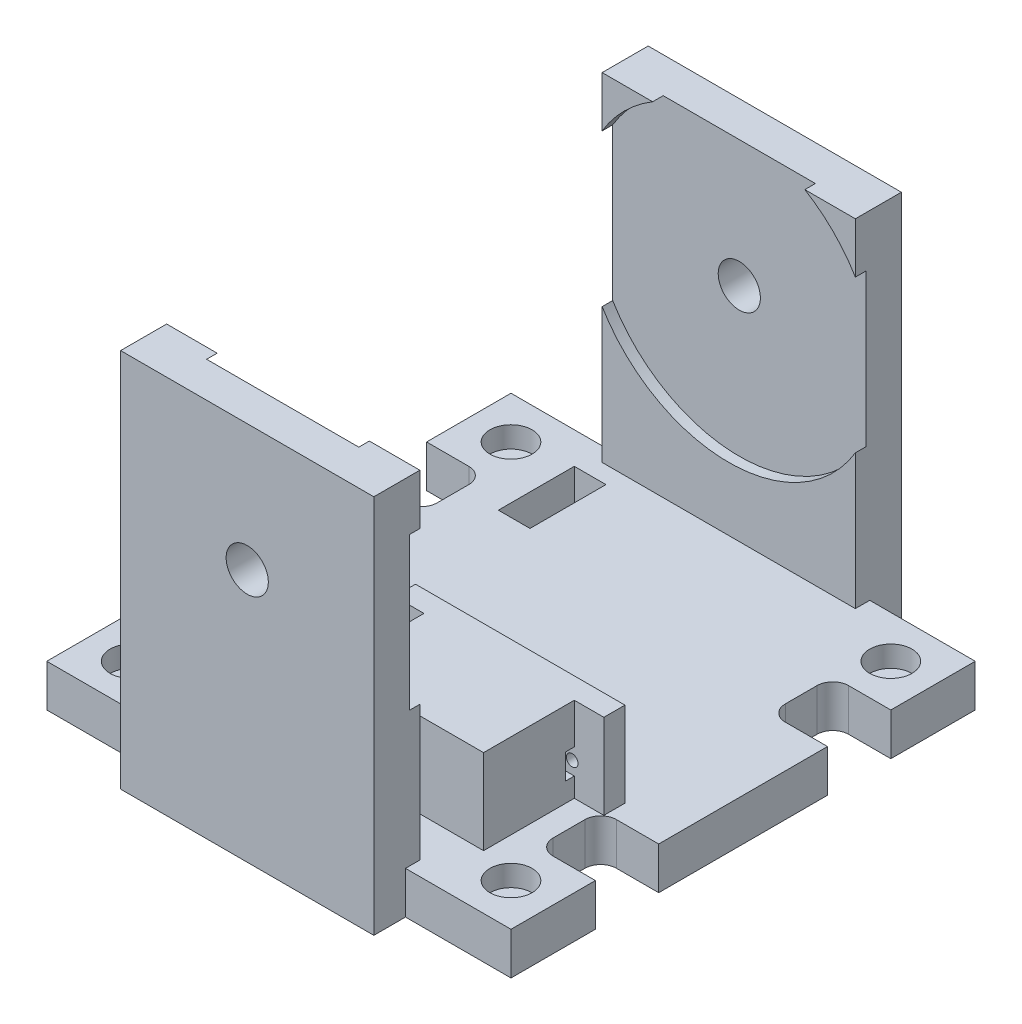
SolidWorks part; units mm, degrees
ref_plane "Front Plane" through (0, 0, 0) normal (0, 0, 1) x (1, 0, 0)
ref_plane "Top Plane" through (0, 0, 0) normal (0, 1, 0) x (1, 0, 0)
ref_plane "Right Plane" through (0, 0, 0) normal (1, 0, 0) x (0, 0, -1)
sketch "Sketch1" plane through (0, 0, 0) normal (0, 1, 0) x (1, 0, 0)
  line L0 (-44, 28) -> (-36, 28)
  line L1 (44, -44) -> (-44, -44)
  line L2 (44, -44) -> (44, 44) construction
  line L3 (44, 44) -> (-44, 44)
  line L4 (-44, -44) -> (-44, 44) construction
  line L5 (44, -44) -> (-44, 44) construction
  line L6 (44, 44) -> (-44, -44) construction
  line L7 (-33, 25) -> (-33, -25) construction
  line L8 (-36, -28) -> (-44, -28)
  line L9 (-33, 0) -> (0, 0) construction
  line L10 (0, 44) -> (0, -44) construction
  line L11 (-44, 28) -> (-44, 44)
  line L12 (-44, -28) -> (-44, -44)
  line L13 (44, -28) -> (44, -44)
  line L14 (44, 28) -> (44, 44)
  line L15 (36, -28) -> (44, -28)
  line L16 (33, 25) -> (33, -25) construction
  line L17 (44, 28) -> (36, 28)
  line L18 (-33, 25) -> (-33, 19)
  line L19 (-36, 16) -> (-44, 16)
  line L20 (-44, 16) -> (-44, -16)
  line L21 (-44, -16) -> (-36, -16)
  line L22 (-33, -19) -> (-33, -25)
  line L23 (33, -19) -> (33, -25)
  line L24 (44, -16) -> (36, -16)
  line L25 (44, 16) -> (44, -16)
  line L26 (36, 16) -> (44, 16)
  line L27 (33, 19) -> (33, 25)
  arc A0 (-36, 28) -> (-33, 25) centre (-36, 25) cw
  arc A1 (-33, -25) -> (-36, -28) centre (-36, -25) cw
  arc A2 (33, -25) -> (36, -28) centre (36, -25) ccw
  arc A3 (36, 28) -> (33, 25) centre (36, 25) ccw
  arc A4 (-33, 19) -> (-36, 16) centre (-36, 19) cw
  arc A5 (-36, -16) -> (-33, -19) centre (-36, -19) cw
  arc A6 (36, -16) -> (33, -19) centre (36, -19) ccw
  arc A7 (33, 19) -> (36, 16) centre (36, 19) ccw
  point P0 (0, 0)
  dimension "D1" = 88
  dimension "D2" = 16
  dimension "D3" = 8
  dimension "D4" = 3
  dimension "D5" = 12
  dimension "D6" = 12
extrude "Boss-Extrude1" add sketch "Sketch1" along normal blind 8
sketch "Sketch2" plane through (0, 8, 0) normal (0, 1, 0) x (1, 0, 0)
  line L0 (-44, 44) -> (-44, 28) construction
  line L1 (44, 44) -> (-44, 44) construction
  line L2 (-44, 0) -> (0, 0) construction
  line L3 (-44, 16) -> (-44, -16) construction
  line L4 (0, 0) -> (0, 44) construction
  circle A0 centre (-36, 36) radius 1.651
  circle A1 centre (36, 36) radius 1.651
  circle A2 centre (36, -36) radius 1.651
  circle A3 centre (-36, -36) radius 1.651
  dimension "D3" = 3.302
  dimension "D1" = 8
  dimension "D2" = 8
extrude "Cut-Extrude1" cut sketch "Sketch2" against normal through all
sketch "Sketch3" plane through (0, 8, 0) normal (0, 1, 0) x (1, 0, 0)
  circle A0 centre (-36, 36) radius 4
  circle A1 centre (36, 36) radius 4
  circle A2 centre (36, -36) radius 4
  circle A3 centre (-36, -36) radius 4
  dimension "D1" = 8
extrude "Cut-Extrude2" cut sketch "Sketch3" against normal blind 4
sketch "Sketch4" plane through (0, 8, 0) normal (0, 1, 0) x (1, 0, 0)
  line L0 (0, -12.5) -> (3, -12.5)
  line L1 (28.5, -33.7) -> (0, -33.7)
  line L2 (28.5, -33.7) -> (28.5, -12.5) construction
  line L3 (28.5, -12.5) -> (0, -12.5) construction
  line L4 (0, -33.7) -> (0, -12.5) construction
  line L5 (28.5, -33.7) -> (0, -12.5) construction
  line L6 (28.5, -12.5) -> (0, -33.7) construction
  line L7 (3, -12.5) -> (3, -30.7)
  line L8 (3, -30.7) -> (25.5, -30.7)
  line L9 (25.5, -30.7) -> (25.5, -12.5)
  line L10 (25.5, -12.5) -> (28.5, -12.5)
  line L11 (0, -12.5) -> (-5.6, -12.5)
  line L12 (-5.6, -12.5) -> (-5.6, -16.5)
  line L13 (-5.6, -16.5) -> (0, -16.5)
  line L14 (0, -16.5) -> (0, -33.7)
  line L15 (28.5, -12.5) -> (34.1, -12.5)
  line L16 (34.1, -12.5) -> (34.1, -16.5)
  line L17 (34.1, -16.5) -> (28.5, -16.5)
  line L18 (28.5, -16.5) -> (28.5, -33.7)
  point P0 (14.25, -23.1)
  dimension "D1" = 28.5
  dimension "D2" = 21.2
  dimension "D3" = 33.7
  dimension "D4" = 3
  dimension "D5" = 3
  dimension "D6" = 4
  dimension "D7" = 5.6
extrude "Boss-Extrude2" add sketch "Sketch4" along normal blind 12.1
sketch "Sketch5" plane through (0, 20.1, 0) normal (0, 1, 0) x (1, 0, 0)
  line L0 (3, -12.5) -> (25.5, -12.5)
  line L12 (3, -12.5) -> (-5.6, -12.5)
  line L13 (-5.6, -12.5) -> (-5.6, -16.5)
  line L14 (-5.6, -16.5) -> (0, -16.5)
  line L15 (0, -16.5) -> (0, -33.7)
  line L16 (0, -33.7) -> (28.5, -33.7)
  line L17 (28.5, -33.7) -> (28.5, -16.5)
  line L18 (28.5, -16.5) -> (34.1, -16.5)
  line L19 (34.1, -16.5) -> (34.1, -12.5)
  line L20 (34.1, -12.5) -> (25.5, -12.5)
  line L21 (25.5, -12.5) -> (25.5, -30.7)
  line L22 (25.5, -30.7) -> (3, -30.7)
  line L23 (3, -30.7) -> (3, -12.5)
  line L24 (3, -12.5) -> (-5.6, -12.5)
  line L25 (-5.6, -12.5) -> (-5.6, -16.5)
  line L26 (-5.6, -16.5) -> (0, -16.5)
  line L27 (0, -16.5) -> (0, -33.7)
  line L28 (0, -33.7) -> (28.5, -33.7)
  line L29 (28.5, -33.7) -> (28.5, -16.5)
  line L30 (28.5, -16.5) -> (34.1, -16.5)
  line L31 (34.1, -16.5) -> (34.1, -12.5)
  line L32 (34.1, -12.5) -> (25.5, -12.5)
  line L33 (25.5, -12.5) -> (25.5, -30.7) construction
  line L34 (25.5, -30.7) -> (3, -30.7) construction
  line L35 (3, -30.7) -> (3, -12.5) construction
  dimension "D1" = 0
extrude "Boss-Extrude3" add sketch "Sketch5" along normal blind 4
sketch "Sketch6" plane through (0, 0, 12.5) normal (0, 0, -1) x (-1, 0, 0)
  line L0 (-28.1, 14.05) -> (-0.4, 14.05) construction
  line L1 (-25.5, 20.1) -> (-25.5, 8) construction
  line L2 (-14.25, 14.05) -> (-14.25, 8) construction
  line L3 (-25.5, 8) -> (-3, 8) construction
  circle A0 centre (-28.1, 14.05) radius 1.1
  circle A1 centre (-0.4, 14.05) radius 1.1
  point P4 (-25.5, 14.05)
  dimension "D1" = 2.2
  dimension "D2" = 27.7
extrude "Cut-Extrude4" cut sketch "Sketch6" against normal blind 4
sketch "Sketch7" plane through (28.5, 0, 0) normal (1, 0, 0) x (0, 0, -1)
  line L1 (-18.1764, 16.4376) -> (-16.5, 16.4376)
  line L2 (-18.1764, 16.4376) -> (-18.1764, 11.6624)
  line L3 (-18.1764, 11.6624) -> (-16.5, 11.6624)
  line L4 (-16.5, 16.4376) -> (-16.5, 11.6624)
  line L5 (-18.1764, 16.4376) -> (-16.5, 11.6624) construction
  line L6 (-18.1764, 11.6624) -> (-16.5, 16.4376) construction
  line L7 (-16.5, 13.0253) -> (-16.5, 8) construction
  line L8 (-12.5, 12.95) -> (-12.5, 15.15) construction
  line L9 (-12.5, 12.95) -> (-12.5, 15.15) construction
  line L10 (-17.3382, 14.05) -> (-12.5, 14.05) construction
  point P0 (-17.3382, 14.05)
  dimension "D1" = 4.7752
  dimension "D2" = 1.6764
extrude "Cut-Extrude5" cut sketch "Sketch7" against normal through all
sketch "Sketch8" plane through (0, 8, 0) normal (0, 1, 0) x (1, 0, 0)
  line L0 (-44, -44) -> (44, -44) construction
  line L1 (24, 41.275) -> (-24, 41.275)
  line L2 (24, 41.275) -> (24, 44)
  line L3 (24, 44) -> (-24, 44)
  line L4 (-24, 41.275) -> (-24, 44)
  line L5 (24, 41.275) -> (-24, 44) construction
  line L6 (24, 44) -> (-24, 41.275) construction
  line L7 (24, -44) -> (-24, -44)
  line L8 (24, -44) -> (24, -41.275)
  line L9 (24, -41.275) -> (-24, -41.275)
  line L10 (-24, -44) -> (-24, -41.275)
  line L11 (24, -44) -> (-24, -41.275) construction
  line L12 (24, -41.275) -> (-24, -44) construction
  line L13 (44, 44) -> (-44, 44) construction
  line L14 (0, 41.275) -> (0, 0) construction
  point P0 (0, 42.6375)
  point P5 (0, -42.6375)
  dimension "D1" = 82.55
  dimension "D2" = 48
extrude "Boss-Extrude4" add sketch "Sketch8" along normal blind 64
sketch "Sketch9" plane through (0, 0, 44) normal (0, 0, 1) x (1, 0, 0)
  line L0 (-44, 0) -> (44, 0) construction
  line L1 (24, 0) -> (-24, 0)
  line L2 (24, 0) -> (24, 72)
  line L3 (24, 72) -> (-24, 72)
  line L4 (-24, 0) -> (-24, 72)
  line L5 (24, 0) -> (-24, 72) construction
  line L6 (24, 72) -> (-24, 0) construction
  point P0 (0, 36)
extrude "Boss-Extrude5" add sketch "Sketch9" along normal blind 6
mirror "Mirror1" about plane through (0, 0, 0) normal (0, 0, 1) of "Boss-Extrude5"
sketch "Sketch10" plane through (0, 0, 41.275) normal (0, 0, -1) x (-1, 0, 0)
  line L0 (0, 48) -> (0, 0) construction
  line L1 (-24, 72) -> (24, 72) construction
  circle A0 centre (0, 48) radius 28
  dimension "D1" = 56
  dimension "D2" = 24
extrude "Cut-Extrude6" cut sketch "Sketch10" against normal blind 2
sketch "Sketch12" plane through (0, 0, 43.275) normal (0, 0, -1) x (-1, 0, 0)
  line L3 (24, 33.5778) -> (24, 62.4222)
  line L4 (24, 33.5778) -> (24, 62.4222) construction
  line L5 (14.4222, 72) -> (-14.4222, 72)
  line L6 (14.4222, 72) -> (-14.4222, 72) construction
  line L7 (-24, 62.4222) -> (-24, 33.5778)
  line L8 (-24, 62.4222) -> (-24, 33.5778) construction
  circle A0 centre (0, 48) radius 4
  arc A1 (24, 62.4222) -> (14.4222, 72) centre (0, 48) ccw
  arc A2 (24, 62.4222) -> (14.4222, 72) centre (0, 48) ccw construction
  circle A3 centre (0, 48) radius 28 construction
  arc A6 (-14.4222, 72) -> (-24, 62.4222) centre (0, 48) ccw
  arc A7 (-14.4222, 72) -> (-24, 62.4222) centre (0, 48) ccw construction
  arc A8 (-24, 33.5778) -> (24, 33.5778) centre (0, 48) ccw
  arc A9 (-24, 33.5778) -> (24, 33.5778) centre (0, 48) ccw construction
  dimension "D2" = 8
  dimension "D1" = 0
extrude "Cut-Extrude7" cut sketch "Sketch12" against normal through all
mirror "Mirror2" about plane through (0, 0, 0) normal (0, 0, 1) of "Cut-Extrude6", "Cut-Extrude7"
sketch "Sketch13" plane through (0, 0, 0) normal (0, -1, 0) x (1, 0, 0)
  line L0 (-24, -44) -> (-44, -44) construction
  line L1 (-26, -23.6) -> (-20, -23.6)
  line L2 (-26, -23.6) -> (-26, -38)
  line L3 (-26, -38) -> (-20, -38)
  line L4 (-20, -23.6) -> (-20, -38)
  line L5 (-26, -23.6) -> (-20, -38) construction
  line L6 (-26, -38) -> (-20, -23.6) construction
  line L7 (-44, -44) -> (-44, -28) construction
  point P0 (-23, -30.8)
  dimension "D1" = 6
  dimension "D2" = 18
  dimension "D3" = 14.4
  dimension "D4" = 6
extrude "Cut-Extrude8" cut sketch "Sketch13" against normal through all
